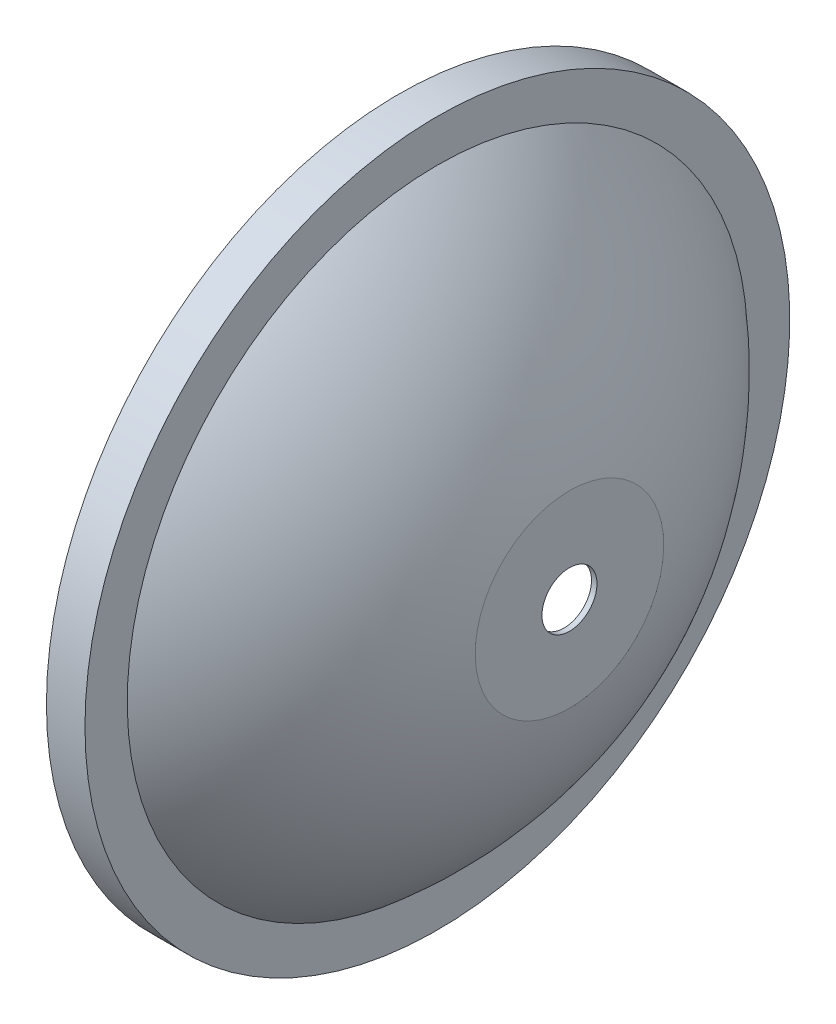
SolidWorks part; units mm, degrees
ref_plane "Front Plane" through (0, 0, 0) normal (0, 0, 1) x (1, 0, 0)
ref_plane "Top Plane" through (0, 0, 0) normal (0, 1, 0) x (1, 0, 0)
ref_plane "Right Plane" through (0, 0, 0) normal (1, 0, 0) x (0, 0, -1)
sketch "Sketch1" plane through (0, 0, 0) normal (0, 0, 1) x (1, 0, 0)
  line L0 (0, 0) -> (17572.9987, 0) construction
  line L1 (-29.993, 63) -> (-23.993, 63)
  line L2 (-23.993, 63) -> (-23.993, 55.857)
  line L3 (0, 5) -> (0, 17)
  line L4 (-29.993, 64) -> (-22.993, 64)
  line L5 (-22.993, 64) -> (-22.993, 56.3205)
  line L6 (1, 5) -> (1, 17.1177)
  line L7 (-29.993, 64) -> (-29.993, 63)
  line L8 (0, 5) -> (1, 5)
  arc A0 (-23.993, 55.857) -> (0, 17) centre (-70.993, 0) cw
  arc A1 (-22.993, 56.3205) -> (1, 17.1177) centre (-70.993, 0) cw
  dimension "D6" = 73
  dimension "D1" = 6
  dimension "D2" = 64
  dimension "D3" = 12
  dimension "D4" = 5
  dimension "D5" = 41
  dimension "D7" = 1
revolve "Revolve1" add sketch "Sketch1" angle 360 about L0
